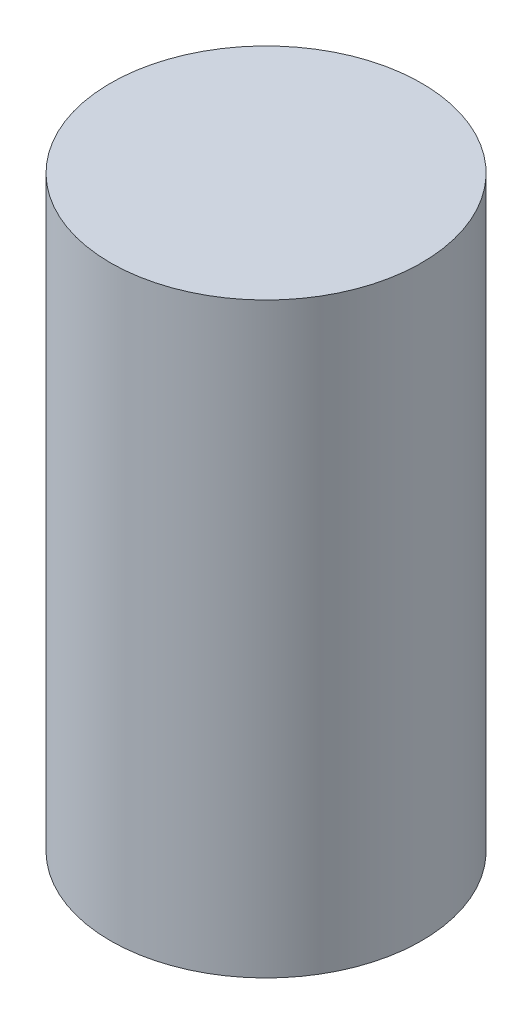
SolidWorks part; units mm, degrees
material "6061 Alloy"
ref_plane "Front Plane" through (0, 0, 0) normal (0, 0, 1) x (1, 0, 0)
ref_plane "Top Plane" through (0, 0, 0) normal (0, 1, 0) x (1, 0, 0)
ref_plane "Right Plane" through (0, 0, 0) normal (1, 0, 0) x (0, 0, -1)
sketch "Sketch1" plane through (0, 0, 0) normal (1, 0, 0) x (0, 0, -1)
  line L0 (0, 0) -> (0, -70675.3676) construction
  line L1 (0, 195.2625) -> (103.5, 195.2625)
  line L2 (103.5, 195.2625) -> (103.5, -195.2625)
  line L3 (103.5, -195.2625) -> (0, -195.2625)
  line L4 (0, -195.2625) -> (0, -183.5531)
  line L5 (0, -183.5531) -> (91.7906, -183.5531)
  line L6 (91.7906, -183.5531) -> (91.7906, 183.5531)
  line L7 (91.7906, 183.5531) -> (0, 183.5531)
  line L8 (0, 183.5531) -> (0, 195.2625)
  line L9 (0, 0) -> (-70675.3676, 0) construction
  line L10 (91.7906, 183.5531) -> (103.5, 183.5531) construction
  dimension "D1" = 11.7094
  dimension "D2" = 103.5
  dimension "D3" = 390.525
revolve "Revolve1" add sketch "Sketch1" angle 360 about L0
